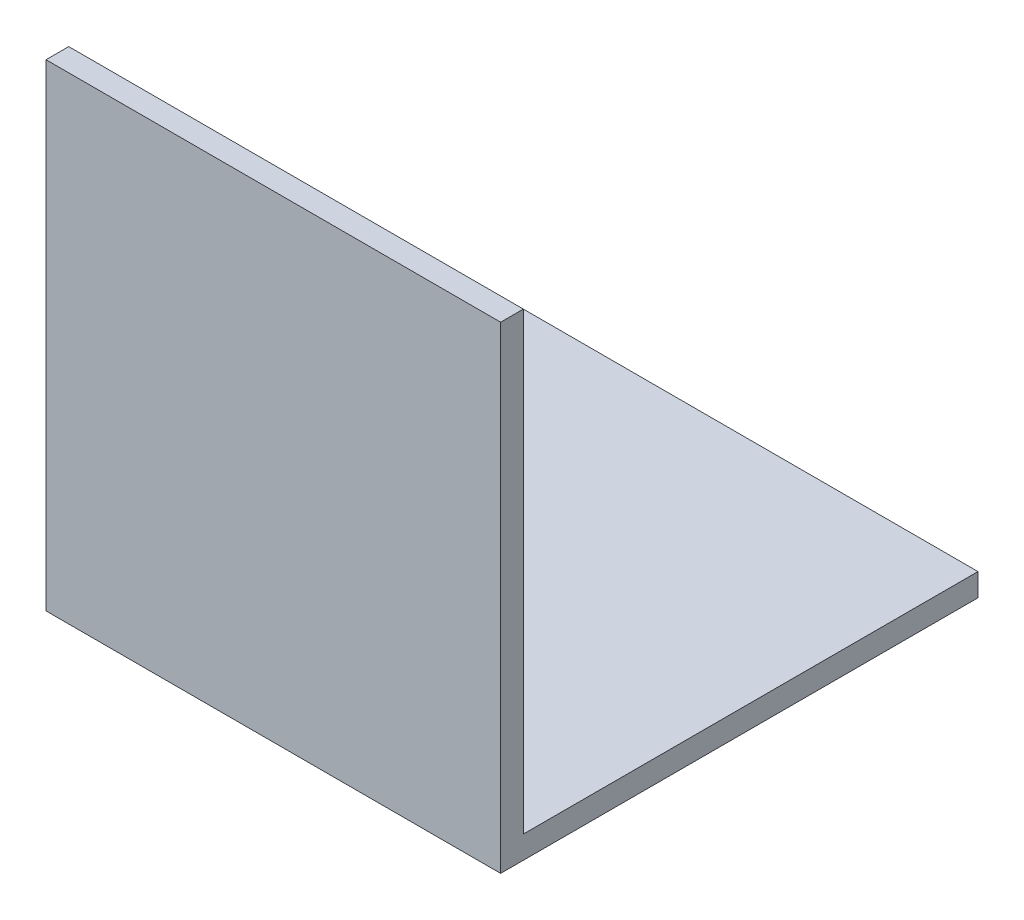
SolidWorks part; units mm, degrees
ref_plane "Front Plane" through (0, 0, 0) normal (0, 0, 1) x (1, 0, 0)
ref_plane "Top Plane" through (0, 0, 0) normal (0, 1, 0) x (1, 0, 0)
ref_plane "Right Plane" through (0, 0, 0) normal (1, 0, 0) x (0, 0, -1)
sketch "Sketch1" plane through (0, 0, 0) normal (0, 1, 0) x (1, 0, 0)
  line L1 (-1000, 779.728) -> (1000, 779.728)
  line L2 (-1000, 779.728) -> (-1000, -1220.272)
  line L3 (-1000, -1220.272) -> (1000, -1220.272)
  line L4 (1000, 779.728) -> (1000, -1220.272)
  line L5 (-1000, 779.728) -> (1000, -1220.272) construction
  line L6 (-1000, -1220.272) -> (1000, 779.728) construction
  point P0 (0, -220.272)
  dimension "D1" = 2000
  dimension "D2" = 2000
extrude "Boss-Extrude1" add sketch "Sketch1" along normal blind 100
sketch "Sketch2" plane through (0, 0, 1220.272) normal (0, 0, 1) x (1, 0, 0)
  line L1 (-1000, 0) -> (1000, 0)
  line L2 (-1000, 0) -> (-1000, 2100)
  line L3 (-1000, 2100) -> (1000, 2100)
  line L4 (1000, 0) -> (1000, 2100)
  dimension "D1" = 2100
extrude "Boss-Extrude2" add sketch "Sketch2" along normal blind 100
